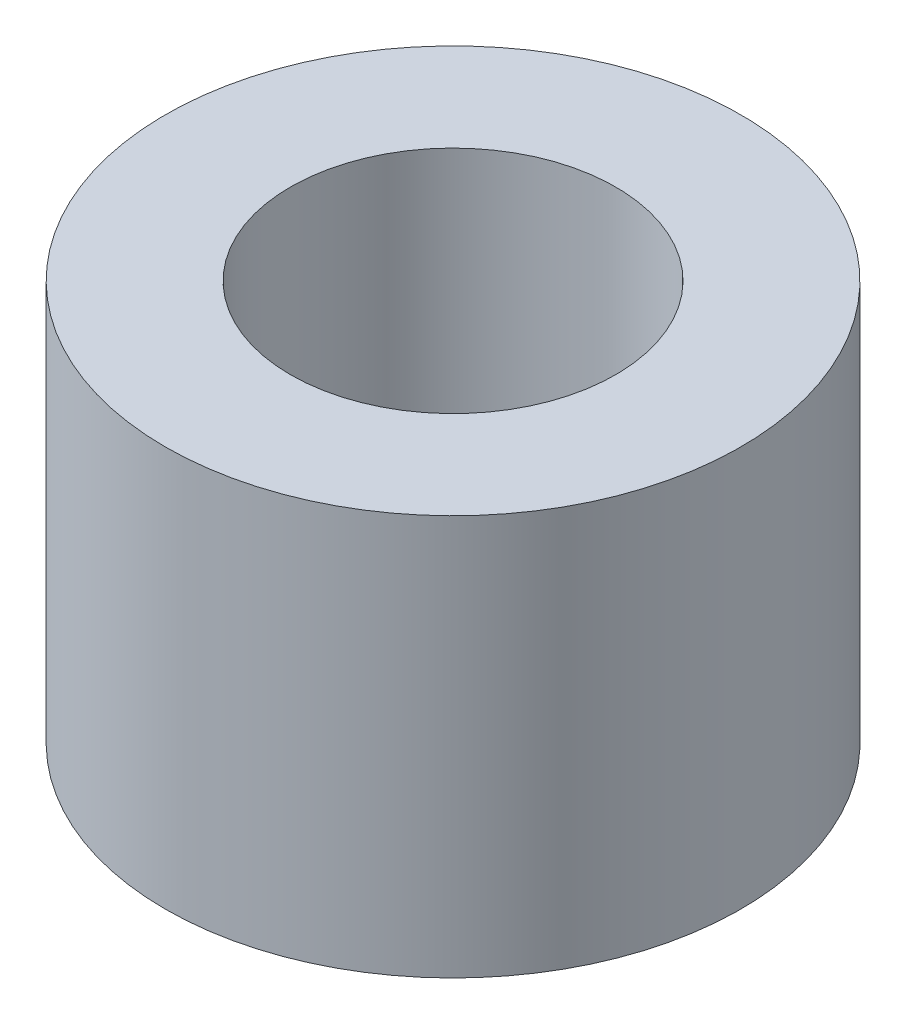
SolidWorks part; units mm, degrees
ref_plane "Front Plane" through (0, 0, 0) normal (0, 0, 1) x (1, 0, 0)
ref_plane "Top Plane" through (0, 0, 0) normal (0, 1, 0) x (1, 0, 0)
ref_plane "Right Plane" through (0, 0, 0) normal (1, 0, 0) x (0, 0, -1)
sketch "Sketch1" plane through (0, 0, 0) normal (0, 1, 0) x (1, 0, 0)
  circle A0 centre (0, 0) radius 1.3
  circle A1 centre (0, 0) radius 2.3
  dimension "D1" = 2.6
  dimension "D2" = 1
extrude "Boss-Extrude1" add sketch "Sketch1" along normal mid plane 3.2
